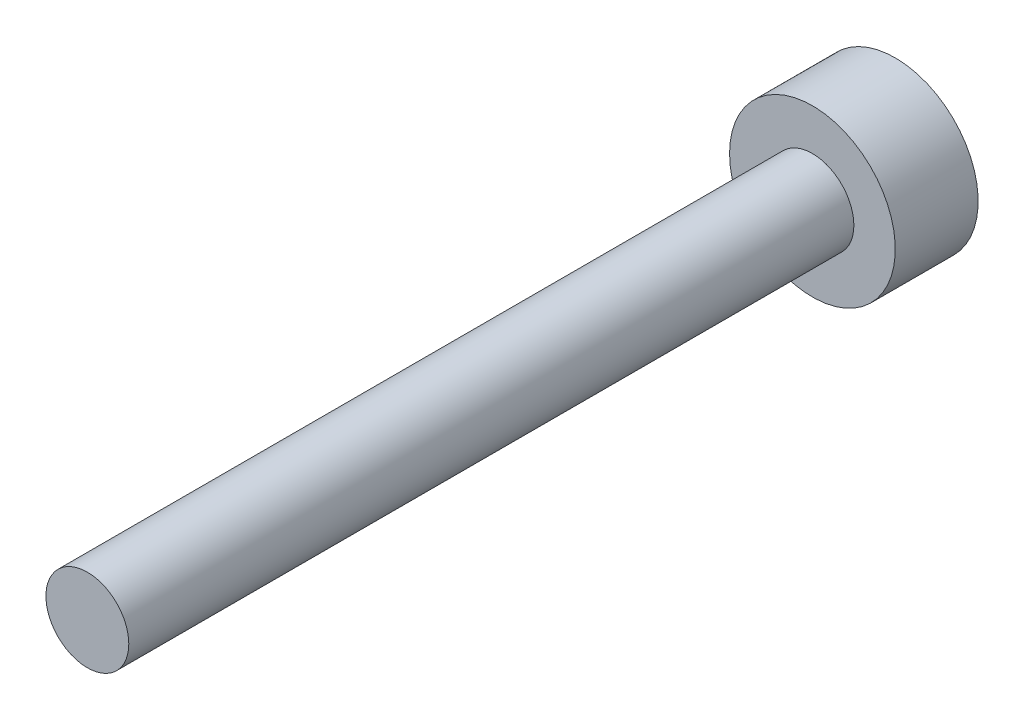
SolidWorks part; units mm, degrees
ref_plane "前视基准面" through (0, 0, 0) normal (0, 0, 1) x (1, 0, 0)
ref_plane "上视基准面" through (0, 0, 0) normal (0, 1, 0) x (1, 0, 0)
ref_plane "右视基准面" through (0, 0, 0) normal (1, 0, 0) x (0, 0, -1)
sketch "草图1" plane through (0, 0, 0) normal (0, 0, 1) x (1, 0, 0)
  circle A0 centre (0, 0) radius 0.4
extrude "凸台-拉伸1" add sketch "草图1" along normal blind 7
sketch "草图2" plane through (0, 0, 0) normal (0, 0, -1) x (-1, 0, 0)
  circle A0 centre (0, 0) radius 0.8
extrude "凸台-拉伸2" add sketch "草图2" along normal blind 0.8
sketch "草图3" plane through (0, 0, -0.8) normal (0, 0, -1) x (-1, 0, 0)
  line L1 (0.4, 0) -> (0.2, 0.3464)
  line L2 (0.2, 0.3464) -> (-0.2, 0.3464)
  line L3 (-0.2, 0.3464) -> (-0.4, 0)
  line L4 (-0.4, 0) -> (-0.2, -0.3464)
  line L5 (-0.2, -0.3464) -> (0.2, -0.3464)
  line L6 (0.2, -0.3464) -> (0.4, 0)
  circle A0 centre (0, 0) radius 0.4 construction
extrude "切除-拉伸1" cut sketch "草图3" against normal blind 0.4
